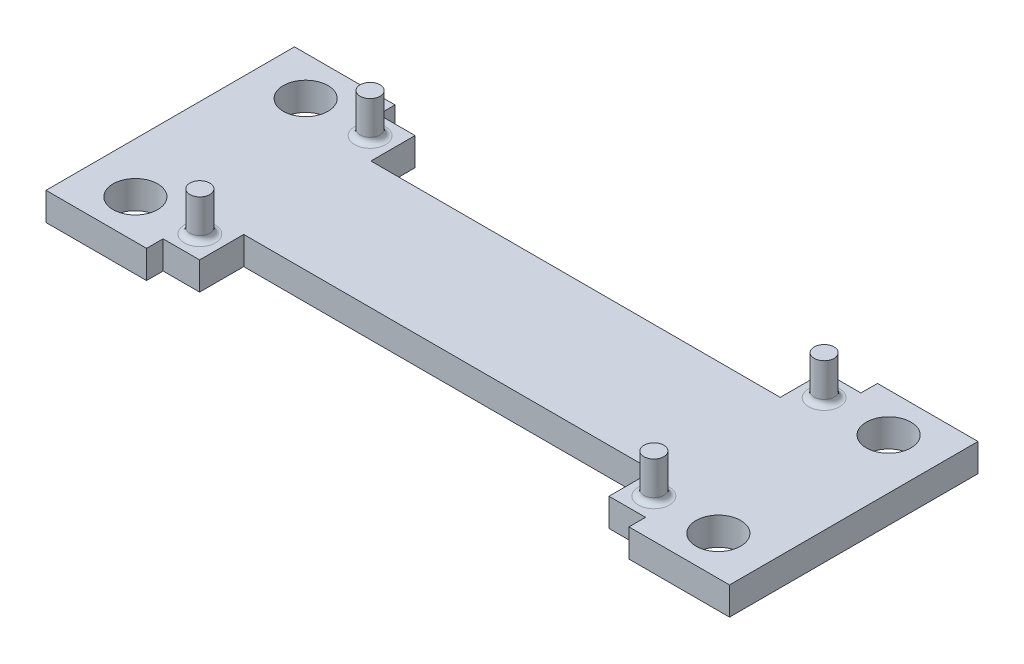
SolidWorks part; units mm, degrees
ref_plane "Front Plane" through (0, 0, 0) normal (0, 0, 1) x (1, 0, 0)
ref_plane "Top Plane" through (0, 0, 0) normal (0, 1, 0) x (1, 0, 0)
ref_plane "Right Plane" through (0, 0, 0) normal (1, 0, 0) x (0, 0, -1)
sketch "Sketch1" plane through (0, 0, 0) normal (0, 1, 0) x (1, 0, 0)
  line L1 (0, 0) -> (43.18, 0)
  line L2 (0, 0) -> (0, 17.78)
  line L3 (0, 17.78) -> (43.18, 17.78)
  line L4 (43.18, 0) -> (43.18, 17.78)
  line L6 (0, 17.78) -> (0, 0)
  line L9 (43.18, 20.01) -> (52.18, 20.01)
  line L10 (43.18, 20.01) -> (43.18, -2.23)
  line L11 (43.18, -2.23) -> (52.18, -2.23)
  line L12 (52.18, 20.01) -> (52.18, -2.23)
  line L13 (0, 20.01) -> (-9, 20.01)
  line L14 (0, 20.01) -> (0, -2.23)
  line L15 (0, -2.23) -> (-9, -2.23)
  line L16 (-9, 20.01) -> (-9, -2.23)
  line L17 (3.27, 17.78) -> (39.91, 17.78)
  line L18 (3.27, 17.78) -> (3.27, 14.58)
  line L19 (3.27, 14.58) -> (39.91, 14.58)
  line L20 (39.91, 17.78) -> (39.91, 14.58)
  line L21 (3.27, 0) -> (39.91, 0)
  line L22 (3.27, 0) -> (3.27, 3.2)
  line L23 (3.27, 3.2) -> (39.91, 3.2)
  line L24 (39.91, 0) -> (39.91, 3.2)
  line L25 (3.27, 17.78) -> (0, 17.78)
  line L26 (3.27, 17.78) -> (3.27, 18.53)
  line L27 (3.27, 18.53) -> (0, 18.53)
  line L28 (0, 17.78) -> (0, 18.53)
  line L29 (3.27, 0) -> (0, 0)
  line L30 (3.27, 0) -> (3.27, -0.75)
  line L31 (3.27, -0.75) -> (0, -0.75)
  line L32 (0, 0) -> (0, -0.75)
  line L33 (39.91, 17.78) -> (43.18, 17.78)
  line L34 (39.91, 17.78) -> (39.91, 18.53)
  line L35 (39.91, 18.53) -> (43.18, 18.53)
  line L36 (43.18, 17.78) -> (43.18, 18.53)
  line L37 (39.91, 0) -> (43.18, 0)
  line L38 (39.91, 0) -> (39.91, -0.75)
  line L39 (39.91, -0.75) -> (43.18, -0.75)
  line L40 (43.18, 0) -> (43.18, -0.75)
  circle A0 centre (1.27, 16.51) radius 0.89
  circle A1 centre (1.27, 1.27) radius 0.89
  circle A2 centre (41.91, 16.51) radius 0.89
  circle A3 centre (41.91, 1.27) radius 0.89
  circle A4 centre (-4.5, 16.51) radius 2
  circle A5 centre (-4.5, 1.27) radius 2
  circle A6 centre (47.68, 1.27) radius 2
  circle A7 centre (47.68, 16.51) radius 2
  dimension "D5" = 1.78
  dimension "D8" = 1.78
  dimension "D11" = 1.78
  dimension "D12" = 1.78
  dimension "D13" = 1.27
  dimension "D14" = 1.27
  dimension "D15" = 4
  dimension "D16" = 4
  dimension "D20" = 0
  dimension "D22" = 4
  dimension "D27" = 4
  dimension "D30" = 0
  dimension "D1" = 43.18
  dimension "D2" = 17.78
  dimension "D3" = 1.27
  dimension "D4" = 1.27
  dimension "D6" = 1.27
  dimension "D7" = 1.27
  dimension "D9" = 1.27
  dimension "D10" = 1.27
  dimension "D17" = 0
  dimension "D18" = 3.5
  dimension "D19" = 0
  dimension "D21" = 3.5
  dimension "D23" = 4.5
  dimension "D24" = 4.5
  dimension "D25" = 0
  dimension "D26" = 0
  dimension "D28" = 4.5
  dimension "D29" = 3.5
  dimension "D31" = 3.5
  dimension "D32" = 4.5
  dimension "D33" = 4.5
  dimension "D34" = 4.5
  dimension "D35" = 3.2
  dimension "D36" = 3.2
  dimension "D37" = 2
  dimension "D38" = 2
  dimension "D39" = 2
  dimension "D40" = 2
  dimension "D41" = 0.75
  dimension "D42" = 0.75
  dimension "D43" = 0.75
  dimension "D44" = 0.75
extrude "Boss-Extrude1" add sketch "Sketch1" along normal blind 2.5 contours L24 L1 L4 L3 L20 L19 L18 L2 L22 L23 A3 A2 A1 A0 | L13 L16 L15 L14 L2 A5 A4 | L12 L9 L10 L4 L11 A7 A6 | L38 L39 L10 L1 | L35 L34 L3 L10 | L26 L27 L14 L3 | L31 L30 L1 L14
sketch "Sketch2" plane through (0, 0, 0) normal (0, -1, 0) x (1, 0, 0)
  circle A0 centre (1.27, -16.51) radius 0.89
  circle A1 centre (1.27, -1.27) radius 0.89
  circle A2 centre (41.91, -16.51) radius 0.89
  circle A3 centre (41.91, -1.27) radius 0.89
  dimension "D1" = 1.78
  dimension "D2" = 1.78
  dimension "D3" = 1.78
  dimension "D4" = 1.78
extrude "Boss-Extrude2" add sketch "Sketch2" against normal blind 6
fillet "Fillet1" radius 0.5 4 edges at (41.91, 2.5, -0.38) (41.91, 2.5, -15.62) (1.27, 2.5, -15.62) (1.27, 2.5, -0.38)
